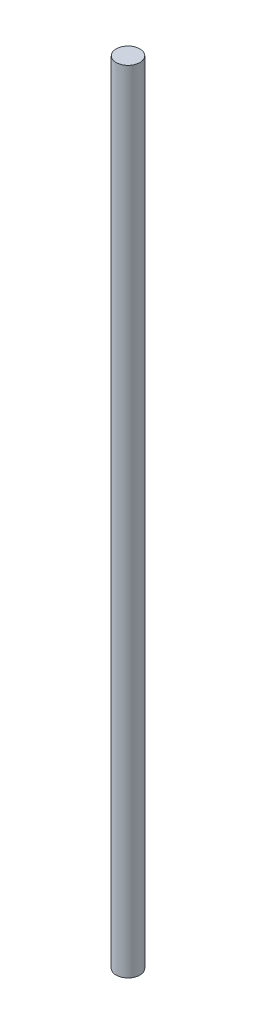
SolidWorks part; units mm, degrees
ref_plane "Front Plane" through (0, 0, 0) normal (0, 0, 1) x (1, 0, 0)
ref_plane "Top Plane" through (0, 0, 0) normal (0, 1, 0) x (1, 0, 0)
ref_plane "Right Plane" through (0, 0, 0) normal (1, 0, 0) x (0, 0, -1)
sketch "Sketch1" plane through (0, 0, 0) normal (0, 1, 0) x (1, 0, 0)
  circle A0 centre (0, 0) radius 1.5
  dimension "D1" = 3
extrude "Length" add sketch "Sketch1" along normal blind 100
